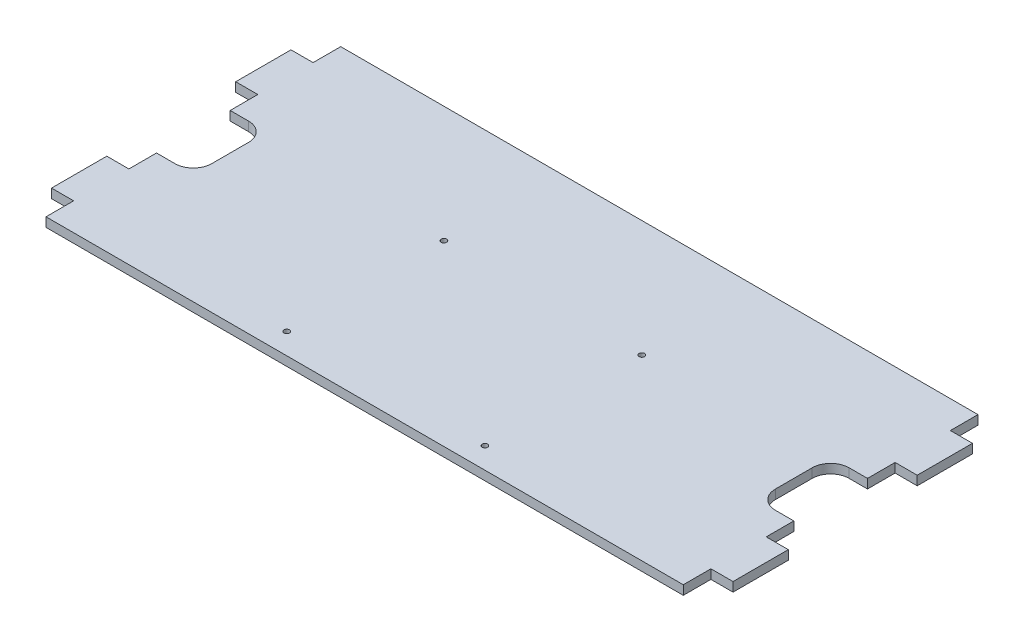
SolidWorks part; units mm, degrees
ref_plane "前基準面" through (0, 0, 0) normal (0, 0, 1) x (1, 0, 0)
ref_plane "上基準面" through (0, 0, 0) normal (0, 1, 0) x (1, 0, 0)
ref_plane "右基準面" through (0, 0, 0) normal (1, 0, 0) x (0, 0, -1)
sketch "草圖1" plane through (0, 0, 0) normal (0, 1, 0) x (1, 0, 0)
  line L0 (173, -65) -> (185, -65)
  line L1 (173, 80) -> (-173, 80)
  line L2 (173, 80) -> (173, 65)
  line L3 (173, -80) -> (-173, -80)
  line L4 (-173, 80) -> (-173, 65)
  line L5 (0, -80) -> (0, 80) construction
  line L6 (173, 0) -> (-173, 0) construction
  line L7 (-173, 65) -> (-185, 65)
  line L9 (-173, 35) -> (-185, 35)
  line L10 (-185, 65) -> (-185, 35)
  line L11 (-173, -35) -> (-185, -35)
  line L13 (-173, -65) -> (-185, -65)
  line L14 (-185, -35) -> (-185, -65)
  line L15 (185, -35) -> (185, -65)
  line L16 (173, -35) -> (185, -35)
  line L18 (173, 35) -> (185, 35)
  line L19 (185, 65) -> (185, 35)
  line L20 (173, 65) -> (185, 65)
  line L22 (-173, 35) -> (-173, -35)
  line L23 (-173, -65) -> (-173, -80)
  line L24 (173, 35) -> (173, -35)
  line L25 (173, -65) -> (173, -80)
  point P0 (0, 0)
  point P23 (0, 0)
  dimension "D1" = 346
  dimension "D2" = 160
  dimension "D3" = 30
  dimension "D4" = 12
  dimension "D5" = 70
extrude "填料-伸長1" add sketch "草圖1" along normal blind 5
sketch "草圖2" plane through (0, 5, 0) normal (0, 1, 0) x (1, 0, 0)
  line L0 (-198.9814, -25.875) -> (243.2492, -25.875) construction
  line L1 (-173, 35) -> (-173, -35) construction
  line L2 (-173, -20) -> (-163, -20)
  line L3 (-173, -20) -> (-173, 20)
  line L4 (-173, 20) -> (-163, 20)
  line L5 (-153, -10) -> (-153, 10)
  line L6 (0, 100.6086) -> (0, -91.6656) construction
  line L7 (173, 20) -> (163, 20)
  line L8 (46.9507, -106.8687) -> (50.0807, -109.5516) construction
  line L9 (153, -10) -> (153, 10)
  line L10 (173, -20) -> (163, -20)
  line L11 (173, -20) -> (173, 20)
  line L12 (-173, -80) -> (173, -80) construction
  line L13 (55, 18) -> (-55, 18) construction
  line L14 (55, 18) -> (55, -70) construction
  line L15 (55, -70) -> (-55, -70) construction
  line L16 (-55, 18) -> (-55, -70) construction
  line L17 (0, -70) -> (0, 18) construction
  arc A0 (-163, -20) -> (-153, -10) centre (-163, -10) ccw
  arc A1 (-163, 20) -> (-153, 10) centre (-163, 10) cw
  arc A2 (163, 20) -> (153, 10) centre (163, 10) ccw
  arc A3 (153, -10) -> (163, -20) centre (163, -10) ccw
  circle A4 centre (-53.75, 16.75) radius 1.25 construction
  circle A8 centre (-53.75, 16.75) radius 1.5
  circle A9 centre (53.75, 16.75) radius 1.5
  circle A10 centre (53.75, -68.5) radius 1.5
  circle A11 centre (-53.75, -68.5) radius 1.5
  point P20 (-153, -20)
  point P23 (-153, 20)
  point P26 (153, 20)
  point P29 (153, -20)
  dimension "D3" = 10
  dimension "D4" = 10
  dimension "D7" = 2.5
  dimension "D8" = 3
  dimension "D1" = 40
  dimension "D2" = 20
  dimension "D5" = 110
  dimension "D6" = 88
  dimension "D9" = 10
extrude "除料-伸長1" cut sketch "草圖2" against normal through all
